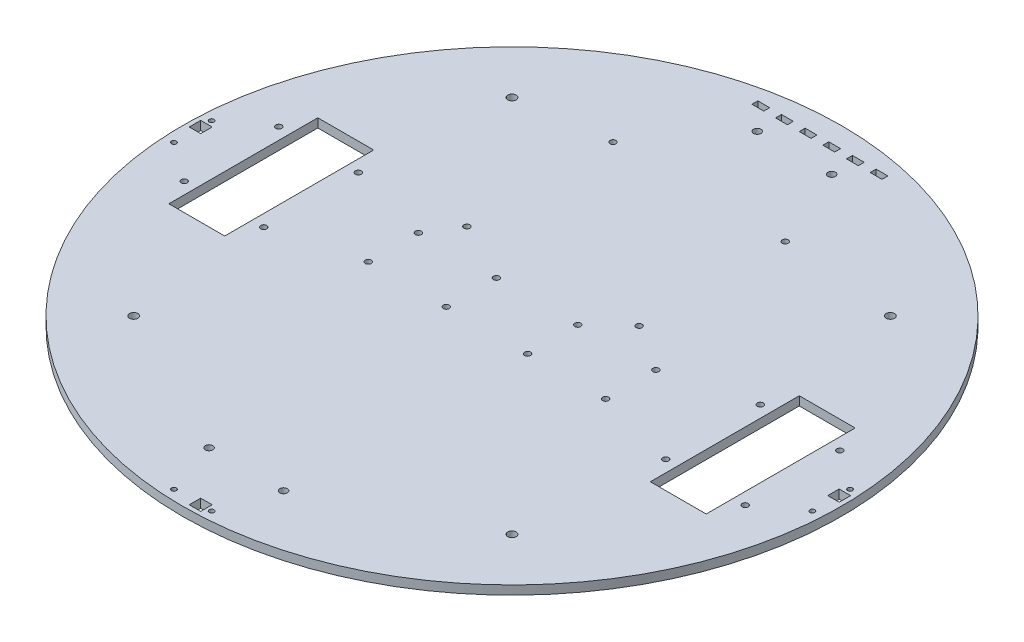
SolidWorks part; units mm, degrees
ref_plane "Front Plane" through (0, 0, 0) normal (0, 0, 1) x (1, 0, 0)
ref_plane "Top Plane" through (0, 0, 0) normal (0, 1, 0) x (1, 0, 0)
ref_plane "Right Plane" through (0, 0, 0) normal (1, 0, 0) x (0, 0, -1)
sketch "Sketch1" plane through (0, 0, 0) normal (0, 1, 0) x (1, 0, 0)
  line L0 (168.375, 7.335) -> (174.525, 7.335)
  line L1 (-144.3, 40) -> (-114.3, 40)
  line L2 (-144.3, 40) -> (-144.3, -40)
  line L3 (-144.3, -40) -> (-114.3, -40)
  line L4 (-114.3, 40) -> (-114.3, -40)
  line L13 (114.3, 40) -> (144.3, 40)
  line L14 (114.3, 40) -> (114.3, -40)
  line L15 (114.3, -40) -> (144.3, -40)
  line L16 (144.3, 40) -> (144.3, -40)
  line L17 (1.185, -168.375) -> (7.335, -168.375)
  line L18 (1.185, -168.375) -> (1.185, -174.525)
  line L19 (1.185, -174.525) -> (7.335, -174.525)
  line L20 (7.335, -168.375) -> (7.335, -174.525)
  line L21 (168.375, 7.335) -> (168.375, 1.185)
  line L22 (168.375, 1.185) -> (174.525, 1.185)
  line L23 (174.525, 7.335) -> (174.525, 1.185)
  line L24 (-174.525, 7.335) -> (-168.375, 7.335)
  line L25 (-174.525, 7.335) -> (-174.525, 1.185)
  line L26 (-174.525, 1.185) -> (-168.375, 1.185)
  line L27 (-168.375, 7.335) -> (-168.375, 1.185)
  line L28 (-21.295, 162.8645) -> (-14.945, 162.8645)
  line L29 (-33.995, 166.0395) -> (-27.645, 166.0395)
  line L30 (-33.995, 166.0395) -> (-33.995, 162.8645)
  line L31 (-33.995, 162.8645) -> (-27.645, 162.8645)
  line L32 (-27.645, 166.0395) -> (-27.645, 162.8645)
  line L33 (-14.945, 166.0395) -> (-14.945, 162.8645)
  line L34 (-21.295, 166.0395) -> (-14.945, 166.0395)
  line L35 (-21.295, 166.0395) -> (-21.295, 162.8645)
  line L36 (-8.595, 162.8645) -> (-2.245, 162.8645)
  line L37 (-2.245, 166.0395) -> (-2.245, 162.8645)
  line L38 (-8.595, 166.0395) -> (-2.245, 166.0395)
  line L39 (-8.595, 166.0395) -> (-8.595, 162.8645)
  line L40 (4.105, 162.8645) -> (10.455, 162.8645)
  line L41 (10.455, 166.0395) -> (10.455, 162.8645)
  line L42 (4.105, 166.0395) -> (10.455, 166.0395)
  line L43 (4.105, 166.0395) -> (4.105, 162.8645)
  line L44 (16.805, 162.8645) -> (23.155, 162.8645)
  line L45 (23.155, 166.0395) -> (23.155, 162.8645)
  line L46 (16.805, 166.0395) -> (23.155, 166.0395)
  line L47 (16.805, 166.0395) -> (16.805, 162.8645)
  line L48 (29.505, 162.8645) -> (35.855, 162.8645)
  line L49 (35.855, 166.0395) -> (35.855, 162.8645)
  line L50 (29.505, 166.0395) -> (35.855, 166.0395)
  line L51 (29.505, 166.0395) -> (29.505, 162.8645)
  circle A0 centre (0, 0) radius 177
  circle A1 centre (-150.65, 25.4) radius 1.6
  circle A2 centre (-150.65, -25.4) radius 1.6
  circle A3 centre (150.65, 25.4) radius 1.6
  circle A4 centre (150.65, -25.4) radius 1.6
  circle A5 centre (-107.95, 25.4) radius 1.6
  circle A6 centre (-107.95, -25.4) radius 1.6
  circle A7 centre (107.95, 25.4) radius 1.6
  circle A8 centre (107.95, -25.4) radius 1.6
  circle A9 centre (-53.7, 107.95) radius 1.6
  circle A10 centre (38.8, 107.95) radius 1.6
  circle A11 centre (-53.7, 29.45) radius 1.6
  circle A12 centre (38.8, 29.45) radius 1.6
  circle A13 centre (-101.6, -101.6) radius 2.2479
  circle A14 centre (101.6, -101.6) radius 2.2479
  circle A15 centre (-101.6, 101.6) radius 2.2479
  circle A16 centre (101.6, 101.6) radius 2.2479
  circle A17 centre (-20, -142.687) radius 2
  circle A18 centre (20, -142.687) radius 2
  circle A19 centre (-20, 151.7193) radius 2
  circle A20 centre (20, 151.7193) radius 2
  circle A21 centre (-10.125, -171.45) radius 1.3
  circle A22 centre (10.125, -171.45) radius 1.3
  circle A23 centre (171.45, -10.125) radius 1.3
  circle A24 centre (171.45, 10.125) radius 1.3
  circle A25 centre (-171.45, -10.125) radius 1.3
  circle A26 centre (-171.45, 10.125) radius 1.3
  circle A27 centre (-63.76, 13.474) radius 1.6
  circle A28 centre (-63.76, -13.45) radius 1.6
  circle A29 centre (-21.85, 13.474) radius 1.6
  circle A30 centre (-21.85, -13.45) radius 1.6
  circle A31 centre (63.76, -13.45) radius 1.6
  circle A32 centre (21.85, -13.45) radius 1.6
  circle A33 centre (21.85, 13.474) radius 1.6
  circle A34 centre (63.76, 13.474) radius 1.6
  point P9 (-114.3, 0)
  point P10 (-0.9618, 0)
  point P11 (-0.9618, 0)
  point P14 (114.3, 0)
  point P26 (-144.3, 0)
  point P27 (144.3, 0)
  dimension "D1" = 354
  dimension "D10" = 3.2
  dimension "D12" = 6.35
  dimension "D13" = 3.2
  dimension "D16" = 6.35
  dimension "D17" = 50.8
  dimension "D20" = 3.2
  dimension "D22" = 3.2
  dimension "D23" = 6.35
  dimension "D24" = 50.8
  dimension "D25" = 25.4
  dimension "D26" = 3.2
  dimension "D27" = 3.2
  dimension "D32" = 3.2
  dimension "D33" = 3.2
  dimension "D34" = 3.2
  dimension "D35" = 3.2
  dimension "D44" = 4.4958
  dimension "D45" = 4.4958
  dimension "D46" = 4.4958
  dimension "D47" = 4.4958
  dimension "D55" = 4
  dimension "D56" = 4
  dimension "D59" = 20
  dimension "D60" = 4
  dimension "D61" = 4
  dimension "D62" = 0
  dimension "D63" = 40
  dimension "D64" = 20
  dimension "D65" = 2.6
  dimension "D66" = 2.6
  dimension "D74" = 171.45
  dimension "D75" = 2.6
  dimension "D76" = 2.6
  dimension "D77" = 0
  dimension "D87" = 2.6
  dimension "D88" = 2.6
  dimension "D90" = 2.79
  dimension "D92" = 0
  dimension "D98" = 3.2
  dimension "D99" = 3.2
  dimension "D100" = 3.2
  dimension "D101" = 3.2
  dimension "D102" = 26.924
  dimension "D103" = 26.924
  dimension "D104" = 41.91
  dimension "D105" = 41.91
  dimension "D106" = 0
  dimension "D110" = 3.2
  dimension "D111" = 3.2
  dimension "D112" = 3.2
  dimension "D113" = 3.2
  dimension "D115" = 41.91
  dimension "D117" = 26.924
  dimension "D119" = 26.924
  dimension "D122" = 3.2
  dimension "D123" = 3.2
  dimension "D2" = 30
  dimension "D3" = 80
  dimension "D4" = 0
  dimension "D5" = 114.3
  dimension "D6" = 30
  dimension "D7" = 80
  dimension "D8" = 0
  dimension "D9" = 114.3
  dimension "D11" = 50.8
  dimension "D14" = 6.35
  dimension "D15" = 25.4
  dimension "D18" = 25.4
  dimension "D19" = 6.35
  dimension "D21" = 6.35
  dimension "D28" = 50.8
  dimension "D29" = 6.35
  dimension "D30" = 6.35
  dimension "D31" = 25.4
  dimension "D36" = 78.5
  dimension "D37" = 78.5
  dimension "D38" = 92.5
  dimension "D39" = 92.5
  dimension "D40" = 0
  dimension "D41" = 0
  dimension "D42" = 38.8
  dimension "D43" = 107.95
  dimension "D48" = 203.2
  dimension "D49" = 203.2
  dimension "D50" = 203.2
  dimension "D51" = 203.2
  dimension "D52" = 0
  dimension "D53" = 101.6
  dimension "D54" = 101.6
  dimension "D57" = 40
  dimension "D58" = 0
  dimension "D67" = 0
  dimension "D68" = 20.25
  dimension "D69" = 10.125
  dimension "D70" = 6.15
  dimension "D71" = 6.15
  dimension "D72" = 2.79
  dimension "D73" = 3.075
  dimension "D78" = 20.25
  dimension "D79" = 10.125
  dimension "D80" = 6.15
  dimension "D81" = 6.15
  dimension "D82" = 2.79
  dimension "D83" = 3.075
  dimension "D84" = 171.45
  dimension "D85" = 6.15
  dimension "D86" = 6.15
  dimension "D89" = 20.25
  dimension "D91" = 3.075
  dimension "D93" = 171.45
  dimension "D94" = 10.125
  dimension "D95" = 3.175
  dimension "D96" = 6.35
  dimension "D107" = 0
  dimension "D108" = 50.54
  dimension "D109" = 26.55
  dimension "D114" = 0
  dimension "D116" = 0
  dimension "D118" = 41.91
  dimension "D120" = 50.54
  dimension "D121" = 26.55
  dimension "D97" = 6
extrude "Boss-Extrude1" add sketch "Sketch1" along normal blind 4.7625
